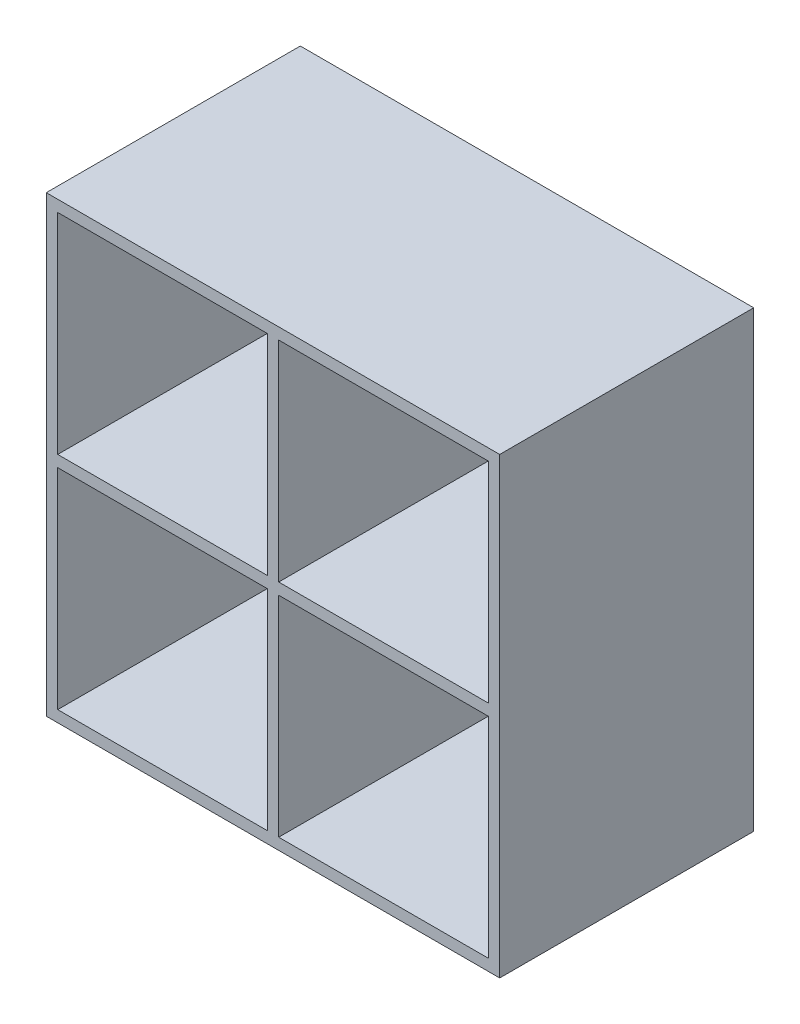
SolidWorks part; units mm, degrees
ref_plane "Front" through (0, 0, 0) normal (0, 0, 1) x (1, 0, 0)
ref_plane "Top" through (0, 0, 0) normal (0, 1, 0) x (1, 0, 0)
ref_plane "Right" through (0, 0, 0) normal (1, 0, 0) x (0, 0, -1)
sketch "Sketch1" plane through (0, 0, 0) normal (0, 0, 1) x (1, 0, 0)
  line L1 (-357, -357) -> (357, -357)
  line L2 (-357, -357) -> (-357, 357)
  line L3 (-357, 357) -> (357, 357)
  line L4 (357, -357) -> (357, 357)
  line L5 (-357, -357) -> (357, 357) construction
  line L6 (-357, 357) -> (357, -357) construction
  line L7 (-339, 9) -> (-9, 9)
  line L8 (-339, 9) -> (-339, 339)
  line L9 (-339, 339) -> (-9, 339)
  line L10 (-9, 9) -> (-9, 339)
  line L11 (-339, 9) -> (-9, 339) construction
  line L12 (-339, 339) -> (-9, 9) construction
  line L13 (9, 9) -> (339, 9)
  line L14 (9, 9) -> (9, 339)
  line L15 (9, 339) -> (339, 339)
  line L16 (339, 9) -> (339, 339)
  line L17 (9, 9) -> (339, 339) construction
  line L18 (9, 339) -> (339, 9) construction
  line L19 (9, -339) -> (339, -339)
  line L20 (9, -339) -> (9, -9)
  line L21 (9, -9) -> (339, -9)
  line L22 (339, -339) -> (339, -9)
  line L23 (9, -339) -> (339, -9) construction
  line L24 (9, -9) -> (339, -339) construction
  line L25 (-9, -339) -> (-339, -339)
  line L26 (-9, -339) -> (-9, -9)
  line L27 (-9, -9) -> (-339, -9)
  line L28 (-339, -339) -> (-339, -9)
  line L29 (-9, -339) -> (-339, -9) construction
  line L30 (-9, -9) -> (-339, -339) construction
  point P0 (0, 0)
  point P6 (-174, 174)
  point P11 (174, 174)
  point P16 (174, -174)
  point P21 (-174, -174)
  dimension "D1" = 330
  dimension "D2" = 330
  dimension "D3" = 330
  dimension "D4" = 330
  dimension "D5" = 330
  dimension "D6" = 330
  dimension "D7" = 330
  dimension "D8" = 330
  dimension "D9" = 18
  dimension "D10" = 18
  dimension "D11" = 18
  dimension "D12" = 18
  dimension "D13" = 18
  dimension "D14" = 714
  dimension "D15" = 18
  dimension "D16" = 714
extrude "Boss-Extrude1" add sketch "Sketch1" against normal blind 400
